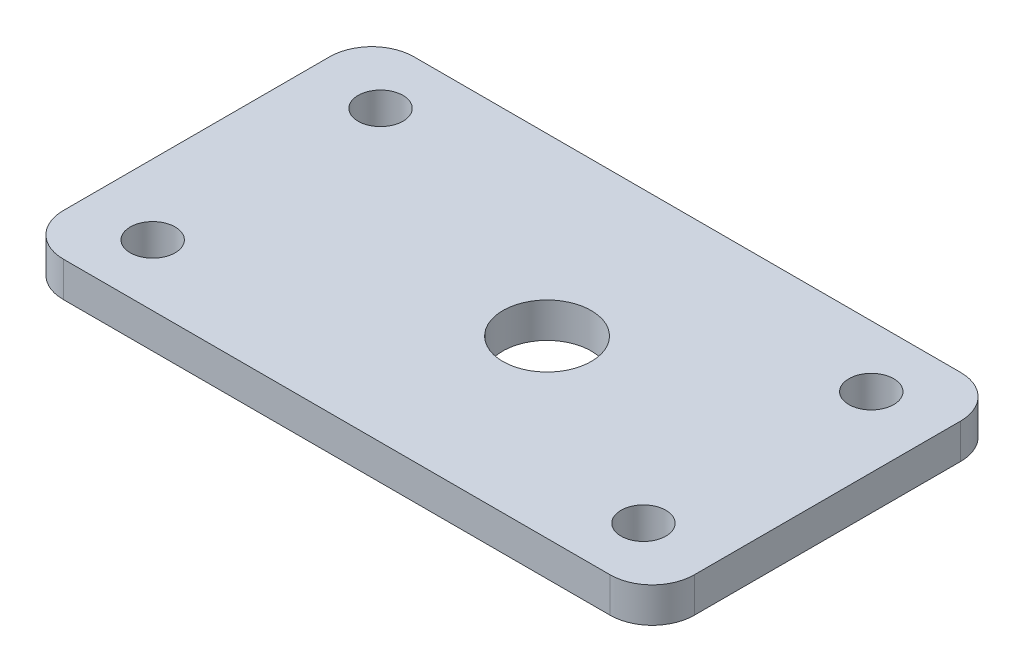
SolidWorks part; units mm, degrees
ref_plane "Front Plane" through (0, 0, 0) normal (0, 0, 1) x (1, 0, 0)
ref_plane "Top Plane" through (0, 0, 0) normal (0, 1, 0) x (1, 0, 0)
ref_plane "Right Plane" through (0, 0, 0) normal (1, 0, 0) x (0, 0, -1)
sketch "Sketch1" plane through (0, 0, 0) normal (0, 1, 0) x (1, 0, 0)
  line L0 (0, 0) -> (3.175, 0) construction
  line L1 (28.575, -15.875) -> (-28.575, -15.875)
  line L2 (28.575, -15.875) -> (28.575, 15.875)
  line L3 (28.575, 15.875) -> (-28.575, 15.875)
  line L4 (-28.575, -15.875) -> (-28.575, 15.875)
  line L5 (28.575, -15.875) -> (-28.575, 15.875) construction
  line L6 (28.575, 15.875) -> (-28.575, -15.875) construction
  circle A2 centre (3.175, 0) radius 4
  point P0 (0, 0)
  dimension "D3" = 8
  dimension "D4" = 31.75
  dimension "D1" = 57.15
  dimension "D2" = 31.75
extrude "Boss-Extrude1" add sketch "Sketch1" along normal blind 3.175
fillet "Fillet1" radius 3.81 4 edges at (28.575, 1.5875, -15.875) (28.575, 1.5875, 15.875) (-28.575, 1.5875, 15.875) (-28.575, 1.5875, -15.875)
sketch "Sketch2" plane through (0, 0, 0) normal (0, -1, 0) x (1, 0, 0)
  circle A0 centre (22.225, -10.3187) radius 2.032 construction
  circle A1 centre (22.225, 10.3188) radius 2.032 construction
  circle A2 centre (-22.225, -10.3187) radius 2.032 construction
  circle A3 centre (-22.225, 10.3188) radius 2.032 construction
  circle A4 centre (22.225, -10.3187) radius 2.032
  circle A5 centre (22.225, 10.3188) radius 2.032
  circle A6 centre (-22.225, -10.3187) radius 2.032
  circle A7 centre (-22.225, 10.3188) radius 2.032
extrude "Cut-Extrude1" cut sketch "Sketch2" against normal through all
